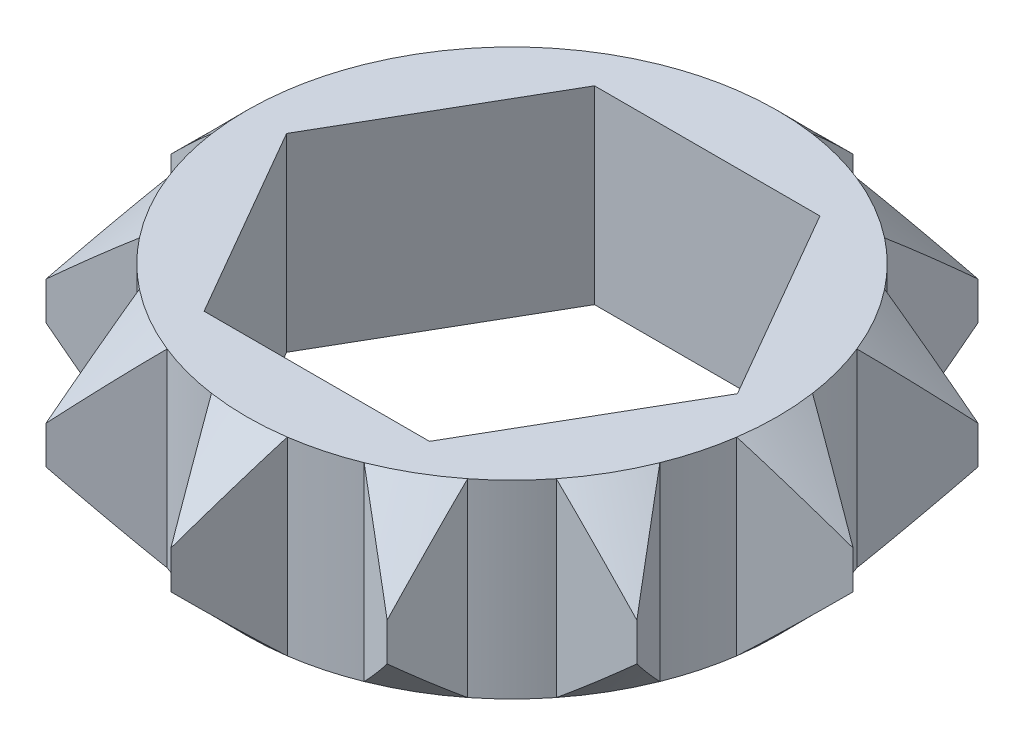
SolidWorks part; units mm, degrees
ref_plane "Front Plane" through (0, 0, 0) normal (0, 0, 1) x (1, 0, 0)
ref_plane "Top Plane" through (0, 0, 0) normal (0, 1, 0) x (1, 0, 0)
ref_plane "Right Plane" through (0, 0, 0) normal (1, 0, 0) x (0, 0, -1)
sketch "Sketch1" plane through (0, 0, 0) normal (0, 1, 0) x (1, 0, 0)
  line L0 (0, -8.89) -> (0, 8.89) construction
  line L1 (7.5523, 0) -> (3.7762, 6.5405)
  line L2 (3.7762, 6.5405) -> (-3.7762, 6.5405)
  line L3 (-3.7762, 6.5405) -> (-7.5523, 0)
  line L4 (-7.5523, 0) -> (-3.7762, -6.5405)
  line L5 (-3.7762, -6.5405) -> (3.7762, -6.5405)
  line L6 (3.7762, -6.5405) -> (7.5523, 0)
  line L7 (0, 8.89) -> (0, 14.3165) construction
  line L8 (0, 11.43) -> (1.27, 8.7988)
  line L9 (0, 11.43) -> (-1.27, 8.7988)
  line L10 (5.715, 9.8987) -> (3.2996, 8.255)
  line L11 (5.715, 9.8987) -> (5.4993, 6.985)
  line L12 (9.8987, 5.715) -> (6.985, 5.4993)
  line L13 (9.8987, 5.715) -> (8.255, 3.2996)
  line L14 (11.43, 0) -> (8.7988, 1.27)
  line L15 (11.43, 0) -> (8.7988, -1.27)
  line L16 (9.8987, -5.715) -> (8.255, -3.2996)
  line L17 (9.8987, -5.715) -> (6.985, -5.4993)
  line L18 (5.715, -9.8987) -> (5.4993, -6.985)
  line L19 (5.715, -9.8987) -> (3.2996, -8.255)
  line L20 (0, -11.43) -> (1.27, -8.7988)
  line L21 (0, -11.43) -> (-1.27, -8.7988)
  line L22 (-5.715, -9.8987) -> (-3.2996, -8.255)
  line L23 (-5.715, -9.8987) -> (-5.4993, -6.985)
  line L24 (-9.8987, -5.715) -> (-6.985, -5.4993)
  line L25 (-9.8987, -5.715) -> (-8.255, -3.2996)
  line L26 (-11.43, 0) -> (-8.7988, -1.27)
  line L27 (-11.43, 0) -> (-8.7988, 1.27)
  line L28 (-9.8987, 5.715) -> (-8.255, 3.2996)
  line L29 (-9.8987, 5.715) -> (-6.985, 5.4993)
  line L30 (-5.715, 9.8987) -> (-5.4993, 6.985)
  line L31 (-5.715, 9.8987) -> (-3.2996, 8.255)
  circle A0 centre (0, 0) radius 6.5405 construction
  circle A1 centre (0, 0) radius 8.89
  point P52 (0, 0)
  dimension "D2" = 17.78
  dimension "D1" = 13.081
  dimension "D3" = 1.27
  dimension "D4" = 2.54
  dimension "D5" = 12
extrude "Boss-Extrude1" add sketch "Sketch1" along normal blind 6.35 contours A1 L6 L5 L4 L3 L2 L1 | A1 L27 L26 | A1 L25 L24 | A1 L23 L22 | A1 L21 L20 | A1 L19 L18 | A1 L17 L16 | A1 L15 L14 | A1 L13 L12 | A1 L11 L10 | A1 L8 L9 | A1 L31 L30 | A1 L29 L28
sketch "Sketch2" plane through (0, 0, 0) normal (0, 0, 1) x (1, 0, 0)
  line L0 (-8.89, 0) -> (-8.89, 6.35)
  line L1 (8.89, 0) -> (-8.89, 0) construction
  line L2 (-11.43, 0) -> (-8.7988, 0) construction
  line L3 (3.7762, 6.35) -> (7.5523, 6.35) construction
  line L4 (-8.89, 6.35) -> (-11.43, 3.81)
  line L5 (-11.43, 6.35) -> (-8.7988, 6.35) construction
  line L6 (-11.43, 6.35) -> (-8.7988, 6.35)
  line L7 (-11.43, 6.35) -> (-11.43, 0)
  line L8 (-8.89, 3.175) -> (-11.43, 3.175) construction
  line L9 (-8.89, 0) -> (-11.43, 2.54)
  line L10 (-11.43, 0) -> (-8.89, 0)
  dimension "D1" = 45
ref_axis "Axis1" through (0, 0, 0) along (0, 1, 0)
revolve "Cut-Revolve1" cut sketch "Sketch2" angle 360 about axis through (0, 0, 0) along (0, 1, 0)
